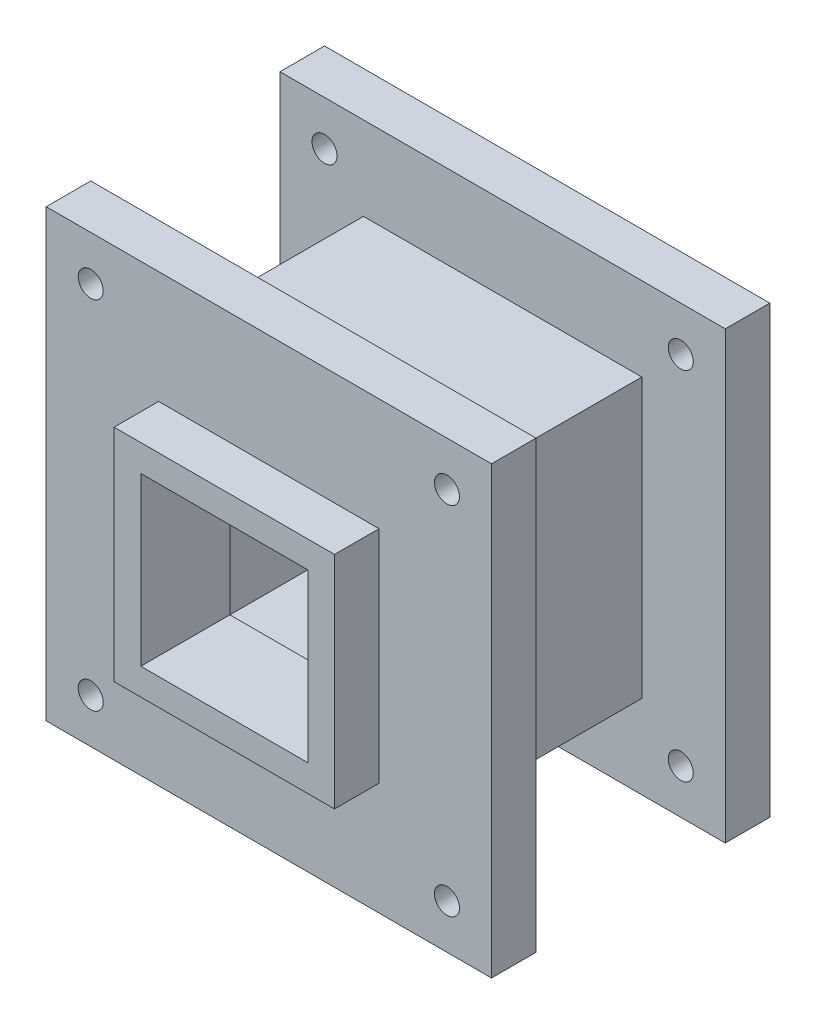
SolidWorks part; units mm, degrees
ref_plane "前视基准面" through (0, 0, 0) normal (0, 0, 1) x (1, 0, 0)
ref_plane "上视基准面" through (0, 0, 0) normal (0, 1, 0) x (1, 0, 0)
ref_plane "右视基准面" through (0, 0, 0) normal (1, 0, 0) x (0, 0, -1)
other "Configuration Table"
sketch "草图1" plane through (0, 0, 0) normal (0, 0, 1) x (1, 0, 0)
  line L1 (-25, -25) -> (25, -25)
  line L2 (-25, -25) -> (-25, 25)
  line L3 (-25, 25) -> (25, 25)
  line L4 (25, -25) -> (25, 25)
  line L6 (-20.2, -20.2) -> (20.2, -20.2)
  line L7 (-20.2, -20.2) -> (-20.2, 20.2)
  line L8 (-20.2, 20.2) -> (20.2, 20.2)
  line L9 (20.2, -20.2) -> (20.2, 20.2)
extrude "50方管壁厚4p8" add sketch "草图1" along normal blind 50
sketch "草图2" plane through (0, 0, 0) normal (0, 0, 1) x (1, 0, 0)
  line L1 (-40, -40) -> (40, -40)
  line L2 (-40, -40) -> (-40, 40)
  line L3 (-40, 40) -> (40, 40)
  line L4 (40, -40) -> (40, 40)
  line L6 (-20.2, -20.2) -> (20.2, -20.2)
  line L7 (-20.2, -20.2) -> (-20.2, 20.2)
  line L8 (-20.2, 20.2) -> (20.2, 20.2)
  line L9 (20.2, -20.2) -> (20.2, 20.2)
extrude "下连接法兰" add sketch "草图2" along normal blind 8
sketch "草图3" plane through (0, 0, 0) normal (0, 0, 1) x (1, 0, 0)
  line L1 (-40, -40) -> (40, -40)
  line L2 (-40, -40) -> (-40, 40)
  line L3 (-40, 40) -> (40, 40)
  line L4 (40, -40) -> (40, 40)
  line L6 (-15, -15) -> (15, -15)
  line L7 (-15, -15) -> (-15, 15)
  line L8 (-15, 15) -> (15, 15)
  line L9 (15, -15) -> (15, 15)
extrude "上连接法兰与承台" add sketch "草图3" along normal blind 8 from offset 42
sketch "草图4" plane through (0, 0, 0) normal (0, 0, 1) x (1, 0, 0)
  line L1 (-19.8, -19.8) -> (19.8, -19.8)
  line L2 (-19.8, -19.8) -> (-19.8, 19.8)
  line L3 (-19.8, 19.8) -> (19.8, 19.8)
  line L4 (19.8, -19.8) -> (19.8, 19.8)
  line L6 (-15, -15) -> (15, -15)
  line L7 (-15, -15) -> (-15, 15)
  line L8 (-15, 15) -> (15, 15)
  line L9 (15, -15) -> (15, 15)
extrude "定位凸台39p6" add sketch "草图4" along normal blind 8 from offset 50
sketch "草图5" plane through (0, 0, 0) normal (0, 0, 1) x (1, 0, 0)
  circle A0 centre (-32, -32) radius 2.25
  circle A1 centre (-32, 32) radius 2.25
  circle A2 centre (32, -32) radius 2.25
  circle A3 centre (32, 32) radius 2.25
extrude "四个M4法兰通孔" cut sketch "草图5" against normal through all and the other way through all
